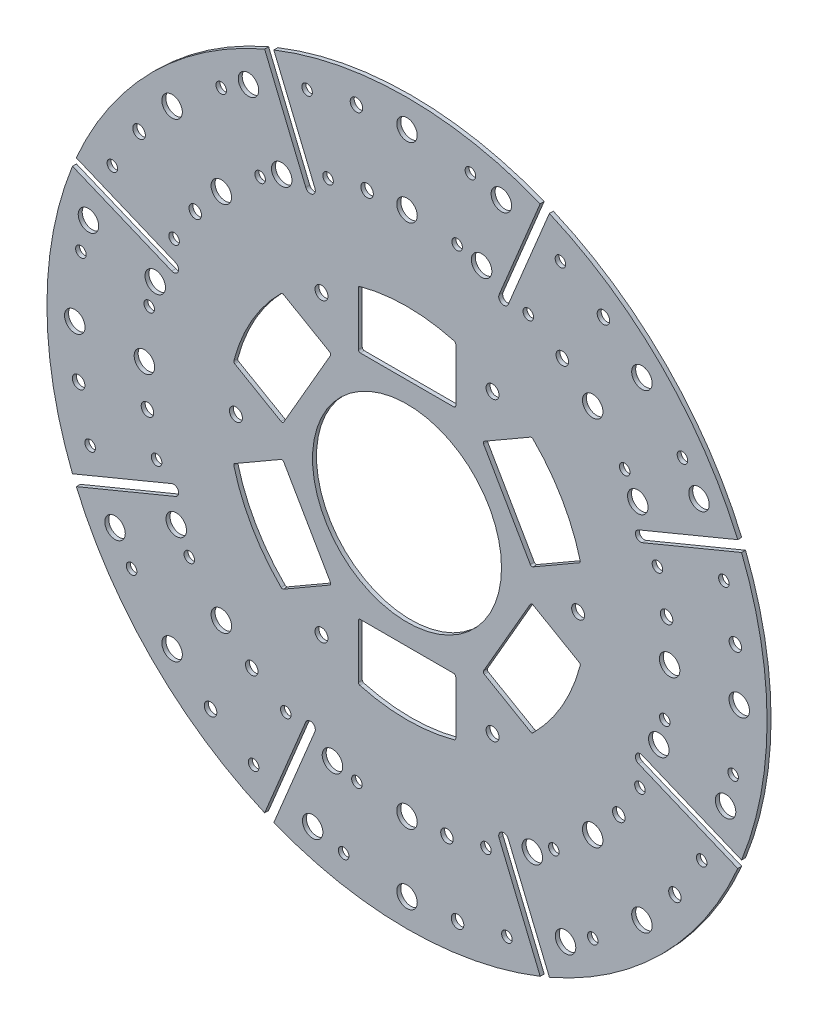
SolidWorks part; units mm, degrees
ref_plane "Plano frontal" through (0, 0, 0) normal (0, 0, 1) x (1, 0, 0)
ref_plane "Plano superior" through (0, 0, 0) normal (0, 1, 0) x (1, 0, 0)
ref_plane "Plano direito" through (0, 0, 0) normal (1, 0, 0) x (0, 0, -1)
sketch "Esboço1" plane through (0, 0, 0) normal (0, 0, 1) x (1, 0, 0)
  circle A0 centre (0, 0) radius 181
  circle A1 centre (0, 0) radius 47.5
extrude "Ressalto-extrusão1" add sketch "Esboço1" along normal blind 2
sketch "Esboço2" plane through (0, 0, 2) normal (0, 0, 1) x (1, 0, 0)
  line L0 (-66.956, -168.1789) -> (-71.5754, -166.2655)
  line L1 (-66.956, -168.1789) -> (-46.2817, -118.2667)
  line L2 (-71.5754, -166.2655) -> (-50.9011, -116.3533)
  line L3 (-69.2657, -167.2222) -> (-48.6008, -117.3327) construction
  line L8 (-166.2655, -71.5754) -> (-168.1789, -66.956)
  line L9 (-166.2655, -71.5754) -> (-116.3533, -50.9011)
  line L10 (-168.1789, -66.956) -> (-118.2667, -46.2817)
  line L11 (-167.2222, -69.2657) -> (-117.3327, -48.6008) construction
  line L16 (-168.1789, 66.956) -> (-166.2655, 71.5754)
  line L17 (-168.1789, 66.956) -> (-118.2667, 46.2817)
  line L18 (-166.2655, 71.5754) -> (-116.3533, 50.9011)
  line L19 (-167.2222, 69.2657) -> (-117.3327, 48.6008) construction
  line L24 (-71.5754, 166.2655) -> (-66.956, 168.1789)
  line L25 (-71.5754, 166.2655) -> (-50.9011, 116.3533)
  line L26 (-66.956, 168.1789) -> (-46.2817, 118.2667)
  line L27 (-69.2657, 167.2222) -> (-48.6008, 117.3327) construction
  line L32 (66.956, 168.1789) -> (71.5754, 166.2655)
  line L33 (66.956, 168.1789) -> (46.2817, 118.2667)
  line L34 (71.5754, 166.2655) -> (50.9011, 116.3533)
  line L35 (69.2657, 167.2222) -> (48.6008, 117.3327) construction
  line L44 (166.2655, 71.5754) -> (168.1789, 66.956)
  line L45 (166.2655, 71.5754) -> (116.3533, 50.9011)
  line L46 (168.1789, 66.956) -> (118.2667, 46.2817)
  line L47 (167.2222, 69.2657) -> (117.3327, 48.6008) construction
  line L52 (168.1789, -66.956) -> (166.2655, -71.5754)
  line L53 (168.1789, -66.956) -> (118.2667, -46.2817)
  line L54 (166.2655, -71.5754) -> (116.3533, -50.9011)
  line L55 (167.2222, -69.2657) -> (117.3327, -48.6008) construction
  line L60 (71.5754, -166.2655) -> (66.956, -168.1789)
  line L61 (71.5754, -166.2655) -> (50.9011, -116.3533)
  line L62 (66.956, -168.1789) -> (46.2817, -118.2667)
  line L63 (69.2657, -167.2222) -> (48.6008, -117.3327) construction
  arc A0 (-46.2817, -118.2667) -> (-50.9011, -116.3533) centre (-48.5914, -117.31) ccw
  arc A2 (-116.3533, -50.9011) -> (-118.2667, -46.2817) centre (-117.31, -48.5914) ccw
  arc A4 (-118.2667, 46.2817) -> (-116.3533, 50.9011) centre (-117.31, 48.5914) ccw
  arc A6 (-50.9011, 116.3533) -> (-46.2817, 118.2667) centre (-48.5914, 117.31) ccw
  arc A8 (46.2817, 118.2667) -> (50.9011, 116.3533) centre (48.5914, 117.31) ccw
  arc A10 (116.3533, 50.9011) -> (118.2667, 46.2817) centre (117.31, 48.5914) ccw
  arc A13 (118.2667, -46.2817) -> (116.3533, -50.9011) centre (117.31, -48.5914) ccw
  arc A15 (50.9011, -116.3533) -> (46.2817, -118.2667) centre (48.5914, -117.31) ccw
  point P116 (0, 0)
extrude "Corte-extrusão1" cut sketch "Esboço2" against normal blind 2
sketch "Esboço4" plane through (0, 0, 2) normal (0, 0, 1) x (1, 0, 0)
  line L0 (0, 0) -> (0, 167) construction
  line L1 (0, 0) -> (-25.4046, 165.0564) construction
  line L2 (0, 0) -> (-50.2179, 159.2707) construction
  line L3 (-47.6347, 115.0003) -> (0, 0) construction
  line L4 (0, 0) -> (47.6347, 115.0003) construction
  line L5 (0, 0) -> (47.4306, 160.1229) construction
  line L6 (0, 0) -> (31.8651, 163.9317) construction
  circle A0 centre (0, 0) radius 132 construction
  circle A1 centre (0, 0) radius 167 construction
  arc A2 (-50.9011, 116.3533) -> (-46.2817, 118.2667) centre (-48.5914, 117.31) ccw construction
  arc A3 (46.2817, 118.2667) -> (50.9011, 116.3533) centre (48.5914, 117.31) ccw construction
  circle A4 centre (0, 167) radius 5.15
  circle A5 centre (0, 132) radius 5.15
  circle A6 centre (47.4306, 160.1229) radius 5.15
  circle A7 centre (37.49, 126.5642) radius 5.15
  circle A8 centre (-25.4046, 165.0564) radius 3.15
  circle A9 centre (-20.0803, 130.4637) radius 3.15
  circle A10 centre (-50.2179, 159.2707) radius 2.65
  circle A11 centre (-39.6932, 125.8906) radius 2.65
  circle A12 centre (25.1868, 129.5748) radius 2.65
  circle A13 centre (31.8651, 163.9317) radius 2.65
  circle A14 centre (118.0868, 118.0868) radius 5.15
  circle A15 centre (93.3381, 93.3381) radius 5.15
  circle A16 centre (146.7625, 79.6855) radius 5.15
  circle A17 centre (116.0039, 62.985) radius 5.15
  circle A18 centre (98.7487, 134.6762) radius 3.15
  circle A19 centre (78.0529, 106.4507) radius 3.15
  circle A20 centre (77.112, 148.1308) radius 2.65
  circle A21 centre (60.9508, 117.0854) radius 2.65
  circle A22 centre (109.433, 73.8135) radius 2.65
  circle A23 centre (138.4493, 93.3852) radius 2.65
  circle A24 centre (167, 0) radius 5.15
  circle A25 centre (132, 0) radius 5.15
  circle A26 centre (160.1229, -47.4306) radius 5.15
  circle A27 centre (126.5642, -37.49) radius 5.15
  circle A28 centre (165.0564, 25.4046) radius 3.15
  circle A29 centre (130.4637, 20.0803) radius 3.15
  circle A30 centre (159.2707, 50.2179) radius 2.65
  circle A31 centre (125.8906, 39.6932) radius 2.65
  circle A32 centre (129.5748, -25.1868) radius 2.65
  circle A33 centre (163.9317, -31.8651) radius 2.65
  circle A34 centre (118.0868, -118.0868) radius 5.15
  circle A35 centre (93.3381, -93.3381) radius 5.15
  circle A36 centre (79.6855, -146.7625) radius 5.15
  circle A37 centre (62.985, -116.0039) radius 5.15
  circle A38 centre (134.6762, -98.7487) radius 3.15
  circle A39 centre (106.4507, -78.0529) radius 3.15
  circle A40 centre (148.1308, -77.112) radius 2.65
  circle A41 centre (117.0854, -60.9508) radius 2.65
  circle A42 centre (73.8135, -109.433) radius 2.65
  circle A43 centre (93.3852, -138.4493) radius 2.65
  circle A44 centre (0, -167) radius 5.15
  circle A45 centre (0, -132) radius 5.15
  circle A46 centre (-47.4306, -160.1229) radius 5.15
  circle A47 centre (-37.49, -126.5642) radius 5.15
  circle A48 centre (25.4046, -165.0564) radius 3.15
  circle A49 centre (20.0803, -130.4637) radius 3.15
  circle A50 centre (50.2179, -159.2707) radius 2.65
  circle A51 centre (39.6932, -125.8906) radius 2.65
  circle A52 centre (-25.1868, -129.5748) radius 2.65
  circle A53 centre (-31.8651, -163.9317) radius 2.65
  circle A54 centre (-118.0868, -118.0868) radius 5.15
  circle A55 centre (-93.3381, -93.3381) radius 5.15
  circle A56 centre (-146.7625, -79.6855) radius 5.15
  circle A57 centre (-116.0039, -62.985) radius 5.15
  circle A58 centre (-98.7487, -134.6762) radius 3.15
  circle A59 centre (-78.0529, -106.4507) radius 3.15
  circle A60 centre (-77.112, -148.1308) radius 2.65
  circle A61 centre (-60.9508, -117.0854) radius 2.65
  circle A62 centre (-109.433, -73.8135) radius 2.65
  circle A63 centre (-138.4493, -93.3852) radius 2.65
  circle A64 centre (-167, 0) radius 5.15
  circle A65 centre (-132, 0) radius 5.15
  circle A66 centre (-160.1229, 47.4306) radius 5.15
  circle A67 centre (-126.5642, 37.49) radius 5.15
  circle A68 centre (-165.0564, -25.4046) radius 3.15
  circle A69 centre (-130.4637, -20.0803) radius 3.15
  circle A70 centre (-159.2707, -50.2179) radius 2.65
  circle A71 centre (-125.8906, -39.6932) radius 2.65
  circle A72 centre (-129.5748, 25.1868) radius 2.65
  circle A73 centre (-163.9317, 31.8651) radius 2.65
  circle A74 centre (-118.0868, 118.0868) radius 5.15
  circle A75 centre (-93.3381, 93.3381) radius 5.15
  circle A76 centre (-79.6855, 146.7625) radius 5.15
  circle A77 centre (-62.985, 116.0039) radius 5.15
  circle A78 centre (-134.6762, 98.7487) radius 3.15
  circle A79 centre (-106.4507, 78.0529) radius 3.15
  circle A80 centre (-148.1308, 77.112) radius 2.65
  circle A81 centre (-117.0854, 60.9508) radius 2.65
  circle A82 centre (-73.8135, 109.433) radius 2.65
  circle A83 centre (-93.3852, 138.4493) radius 2.65
  point P176 (0, 0)
  dimension "D1" = 334
  dimension "D2" = 264
  dimension "D7" = 10.3
  dimension "D8" = 6.3
  dimension "D9" = 5.3
  dimension "D3" = 8.75
  dimension "D4" = 8.75
  dimension "D5" = 6
  dimension "D6" = 11
extrude "Corte-extrusão2" cut sketch "Esboço4" against normal blind 2
sketch "Esboço5" plane through (0, 0, 2) normal (0, 0, 1) x (1, 0, 0)
  line L0 (-24.5, 58) -> (24.5, 58)
  line L1 (-24.5, 58) -> (-24.5, 86.6011)
  line L2 (24.5, 58) -> (24.5, 86.6011)
  line L3 (37.9795, 50.2176) -> (62.4795, 7.7824)
  line L4 (37.9795, 50.2176) -> (62.7487, 64.5182)
  line L5 (62.4795, 7.7824) -> (87.2487, 22.0829)
  line L6 (62.4795, -7.7824) -> (37.9795, -50.2176)
  line L7 (62.4795, -7.7824) -> (87.2487, -22.0829)
  line L8 (37.9795, -50.2176) -> (62.7487, -64.5182)
  line L9 (24.5, -58) -> (-24.5, -58)
  line L10 (24.5, -58) -> (24.5, -86.6011)
  line L11 (-24.5, -58) -> (-24.5, -86.6011)
  line L12 (-37.9795, -50.2176) -> (-62.4795, -7.7824)
  line L13 (-37.9795, -50.2176) -> (-62.7487, -64.5182)
  line L14 (-62.4795, -7.7824) -> (-87.2487, -22.0829)
  line L15 (-62.4795, 7.7824) -> (-37.9795, 50.2176)
  line L16 (-62.4795, 7.7824) -> (-87.2487, 22.0829)
  line L17 (-37.9795, 50.2176) -> (-62.7487, 64.5182)
  arc A0 (62.7487, 64.5182) -> (87.2487, 22.0829) centre (0, 0) cw
  arc A1 (-24.5, 86.6011) -> (24.5, 86.6011) centre (0, 0) cw
  arc A2 (87.2487, -22.0829) -> (62.7487, -64.5182) centre (0, 0) cw
  arc A3 (24.5, -86.6011) -> (-24.5, -86.6011) centre (0, 0) cw
  arc A4 (-62.7487, -64.5182) -> (-87.2487, -22.0829) centre (0, 0) cw
  arc A5 (-87.2487, 22.0829) -> (-62.7487, 64.5182) centre (0, 0) cw
  point P28 (0, 0)
extrude "Corte-extrusão3" cut sketch "Esboço5" against normal blind 2
sketch "Esboço6" plane through (0, 0, 2) normal (0, 0, 1) x (1, 0, 0)
  circle A0 centre (0, 0) radius 86 construction
  circle A2 centre (43, 74.4782) radius 3.25
  circle A4 centre (86, 0) radius 3.25
  circle A6 centre (43, -74.4782) radius 3.25
  circle A8 centre (-43, -74.4782) radius 3.25
  circle A10 centre (-86, 0) radius 3.25
  circle A12 centre (-43, 74.4782) radius 3.25
  point P29 (0, 0)
  dimension "D1" = 172
extrude "Corte-extrusão4" cut sketch "Esboço6" against normal blind 2
fillet "Filete1" radius 1 24 edges at (87.2487, 22.0829, 1) (62.4795, 7.7824, 1) (37.9795, 50.2176, 1) (62.7487, 64.5182, 1) (87.2487, -22.0829, 1) (62.7487, -64.5182, 1) (37.9795, -50.2176, 1) (62.4795, -7.7824, 1) (-24.5, -86.6011, 1) (24.5, -86.6011, 1) (24.5, -58, 1) (-24.5, -58, 1) (-37.9795, -50.2176, 1) (-62.4795, -7.7824, 1) (-87.2487, -22.0829, 1) (-62.7487, -64.5182, 1) (-87.2487, 22.0829, 1) (-62.4795, 7.7824, 1) (-37.9795, 50.2176, 1) (24.5, 58, 1) (-62.7487, 64.5182, 1) (-24.5, 58, 1) (-24.5, 86.6011, 1) (24.5, 86.6011, 1)
